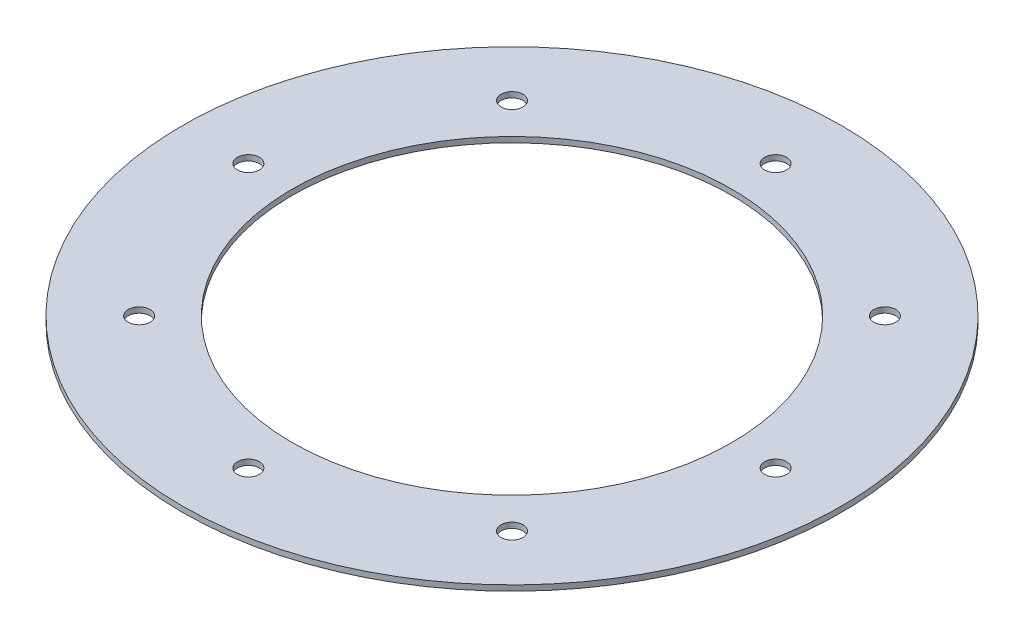
SolidWorks part; units mm, degrees
ref_plane "Front Plane" through (0, 0, 0) normal (0, 0, 1) x (1, 0, 0)
ref_plane "Top Plane" through (0, 0, 0) normal (0, 1, 0) x (1, 0, 0)
ref_plane "Right Plane" through (0, 0, 0) normal (1, 0, 0) x (0, 0, -1)
sketch "Sketch1" plane through (0, 0, 0) normal (0, 1, 0) x (1, 0, 0)
  circle A0 centre (0, 0) radius 60
  circle A1 centre (0, 48) radius 2
  circle A2 centre (33.9411, 33.9411) radius 2
  circle A3 centre (48, 0) radius 2
  circle A4 centre (33.9411, -33.9411) radius 2
  circle A5 centre (0, -48) radius 2
  circle A6 centre (-33.9411, -33.9411) radius 2
  circle A7 centre (-48, 0) radius 2
  circle A8 centre (-33.9411, 33.9411) radius 2
  circle A9 centre (0, 0) radius 40
  point P21 (0, 0)
  dimension "D1" = 120
  dimension "D2" = 48
  dimension "D3" = 8
extrude "Boss-Extrude1" add sketch "Sketch1" along normal blind 1
